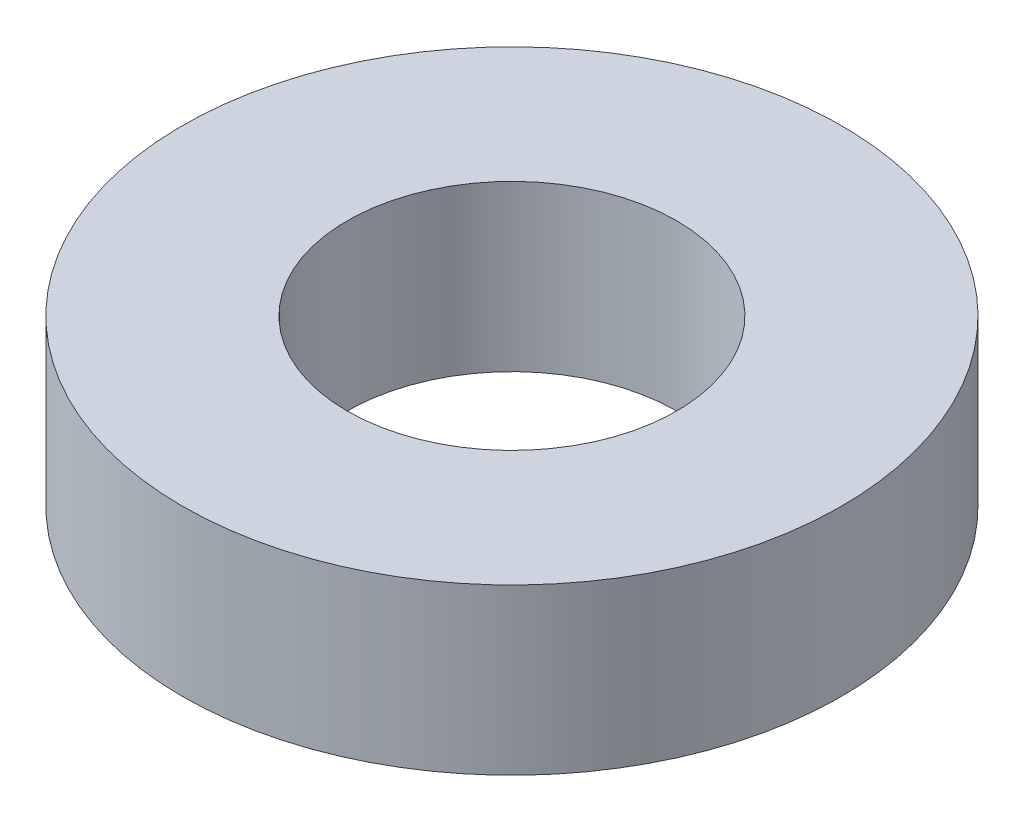
SolidWorks part; units mm, degrees
ref_plane "Plan de face" through (0, 0, 0) normal (0, 0, 1) x (1, 0, 0)
ref_plane "Plan de dessus" through (0, 0, 0) normal (0, 1, 0) x (1, 0, 0)
ref_plane "Plan de droite" through (0, 0, 0) normal (1, 0, 0) x (0, 0, -1)
sketch "Esquisse1" plane through (0, 0, 0) normal (0, 1, 0) x (1, 0, 0)
  circle A0 centre (0, 0) radius 4
  circle A1 centre (0, 0) radius 8
  dimension "D1" = 8
  dimension "D2" = 16
extrude "Boss.-Extru.1" add sketch "Esquisse1" along normal blind 4
